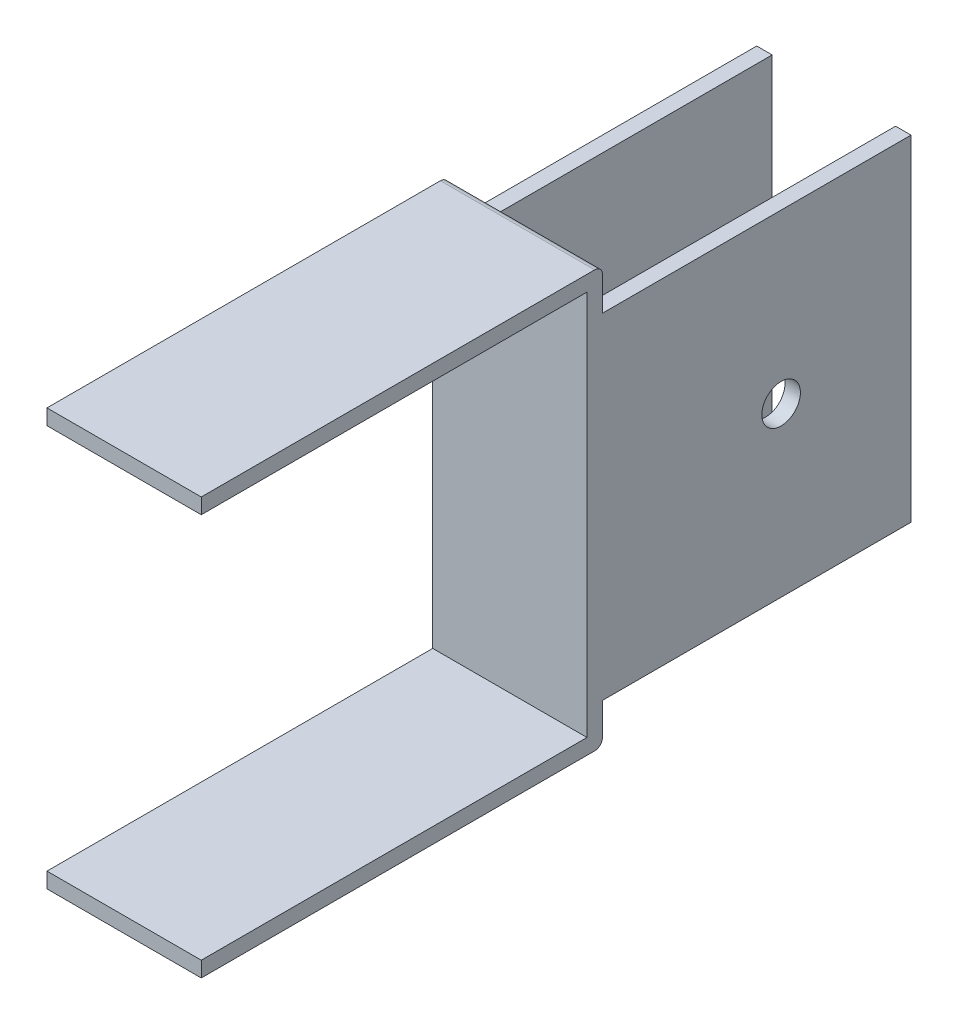
SolidWorks part; units mm, degrees
ref_plane "Front Plane" through (0, 0, 0) normal (0, 0, 1) x (1, 0, 0)
ref_plane "Top Plane" through (0, 0, 0) normal (0, 1, 0) x (1, 0, 0)
ref_plane "Right Plane" through (0, 0, 0) normal (1, 0, 0) x (0, 0, -1)
sketch "Sketch1" plane through (0, 0, 0) normal (0, 0, 1) x (1, 0, 0)
  line L1 (0, 0) -> (20, 0)
  line L2 (0, 0) -> (0, 54)
  line L3 (0, 54) -> (20, 54)
  line L4 (20, 0) -> (20, 54)
  dimension "D1" = 20
  dimension "D2" = 54
extrude "Boss-Extrude1" add sketch "Sketch1" along normal blind 2
sketch "Sketch2" plane through (0, 0, 2) normal (0, 0, 1) x (1, 0, 0)
  line L0 (20, 0) -> (20, 54) construction
  line L1 (0, 54) -> (20, 54)
  line L2 (0, 54) -> (0, 52)
  line L3 (0, 52) -> (20, 52)
  line L4 (20, 54) -> (20, 52)
  line L6 (0, 0) -> (20, 0)
  line L7 (0, 0) -> (0, 2)
  line L8 (0, 2) -> (20, 2)
  line L9 (20, 0) -> (20, 2)
  dimension "D1" = 2
  dimension "D2" = 2
extrude "Boss-Extrude2" add sketch "Sketch2" along normal blind 50
fillet "Fillet1" radius 1 2 edges at (10, 0, 0) (10, 54, 0)
sketch "Sketch3" plane through (0, 0, 0) normal (0, 0, -1) x (-1, 0, 0)
  line L0 (-20, 1) -> (-20, 53) construction
  line L1 (-20, 48.6245) -> (-18, 48.6245)
  line L2 (-20, 48.6245) -> (-20, 5.1576)
  line L3 (-20, 5.1576) -> (-18, 5.1576)
  line L4 (-18, 48.6245) -> (-18, 5.1576)
  line L5 (0, 53) -> (0, 1) construction
  line L6 (0, 48.6245) -> (-2, 48.6245)
  line L7 (0, 48.6245) -> (0, 5.1576)
  line L8 (0, 5.1576) -> (-2, 5.1576)
  line L9 (-2, 48.6245) -> (-2, 5.1576)
  dimension "D1" = 2
  dimension "D2" = 2
extrude "Boss-Extrude3" add sketch "Sketch3" along normal blind 40
sketch "Sketch4" plane through (20, 0, 0) normal (1, 0, 0) x (0, 0, -1)
  line L0 (40, 26.8911) -> (-2, 26.8911) construction
  line L1 (40, 48.6245) -> (40, 5.1576) construction
  line L2 (-2, 2) -> (-2, 52) construction
  circle A0 centre (23.1606, 26.8911) radius 2.5
  dimension "D1" = 5
extrude "Cut-Extrude1" cut sketch "Sketch4" against normal through all
